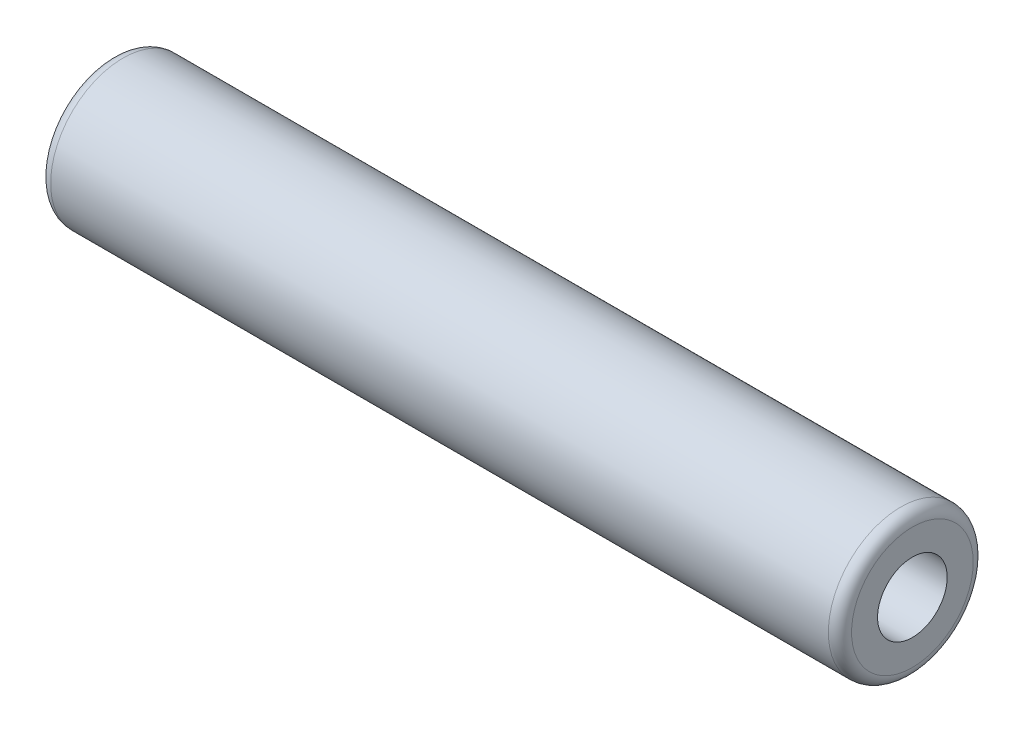
SolidWorks part; units mm, degrees
material "ABS"
ref_plane "Front Plane" through (0, 0, 0) normal (0, 0, 1) x (1, 0, 0)
ref_plane "Top Plane" through (0, 0, 0) normal (0, 1, 0) x (1, 0, 0)
ref_plane "Right Plane" through (0, 0, 0) normal (1, 0, 0) x (0, 0, -1)
sketch "Sketch1" plane through (0, 0, 0) normal (1, 0, 0) x (0, 0, -1)
  circle A0 centre (0, 0) radius 9.906
  circle A1 centre (0, 0) radius 4.7625
  dimension "D1" = 19.812
  dimension "D2" = 9.525
extrude "Boss-Extrude1" add sketch "Sketch1" along normal blind 109.5375
fillet "Fillet1" radius 1.5875 2 edges at (0, 0, -9.906) (109.5375, 0, -9.906)
